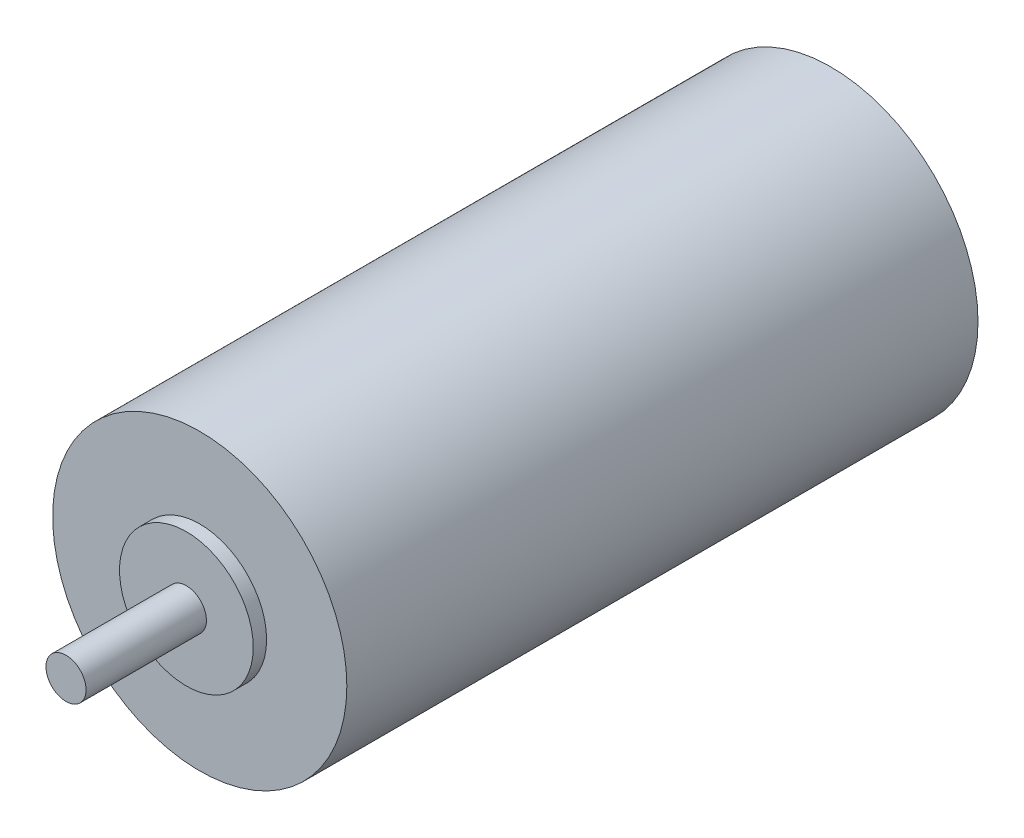
SolidWorks part; units mm, degrees
ref_plane "Front Plane" through (0, 0, 0) normal (0, 0, 1) x (1, 0, 0)
ref_plane "Top Plane" through (0, 0, 0) normal (0, 1, 0) x (1, 0, 0)
ref_plane "Right Plane" through (0, 0, 0) normal (1, 0, 0) x (0, 0, -1)
sketch "Sketch1" plane through (0, 0, 0) normal (0, 0, 1) x (1, 0, 0)
  circle A0 centre (0, 0) radius 11
  dimension "D1" = 22
extrude "Boss-Extrude1" add sketch "Sketch1" along normal blind 47.2
sketch "Sketch2" plane through (0, 0, 0) normal (1, 0, 0) x (0, 0, -1)
  line L0 (-47.2, 11) -> (-47.2, -11) construction
  line L1 (-47.2, 0) -> (-48.2, 0)
  line L2 (-47.2, 0) -> (-47.2, 5)
  line L3 (-47.2, 5) -> (-48.2, 5)
  line L4 (-48.2, 0) -> (-48.2, 5)
  dimension "D1" = 1
  dimension "D2" = 5
ref_axis "Axis1" through (0, 0, 47.2) along (0, 0, -1)
revolve "Revolve1" add sketch "Sketch2" angle 360 about axis through (0, 0, 47.2) along (0, 0, -1)
sketch "Sketch3" plane through (0, 0, 0) normal (1, 0, 0) x (0, 0, -1)
  line L1 (0, 0) -> (2.3, 0)
  line L2 (0, 0) -> (0, 3)
  line L3 (0, 3) -> (2.3, 3)
  line L4 (2.3, 0) -> (2.3, 3)
  dimension "D1" = 3
  dimension "D2" = 2.3
revolve "Revolve2" add sketch "Sketch3" angle 360 about axis through (0, 0, 47.2) along (0, 0, -1)
sketch "Sketch4" plane through (0, 0, 48.2) normal (0, 0, 1) x (1, 0, 0)
  circle A0 centre (0, 0) radius 1.5
  dimension "D1" = 3
extrude "Boss-Extrude2" add sketch "Sketch4" along normal blind 9
sketch "Sketch5" plane through (0, 0, -2.3) normal (0, 0, -1) x (-1, 0, 0)
  circle A0 centre (0, 0) radius 1
  dimension "D1" = 2
extrude "Boss-Extrude3" add sketch "Sketch5" along normal blind 2.65
